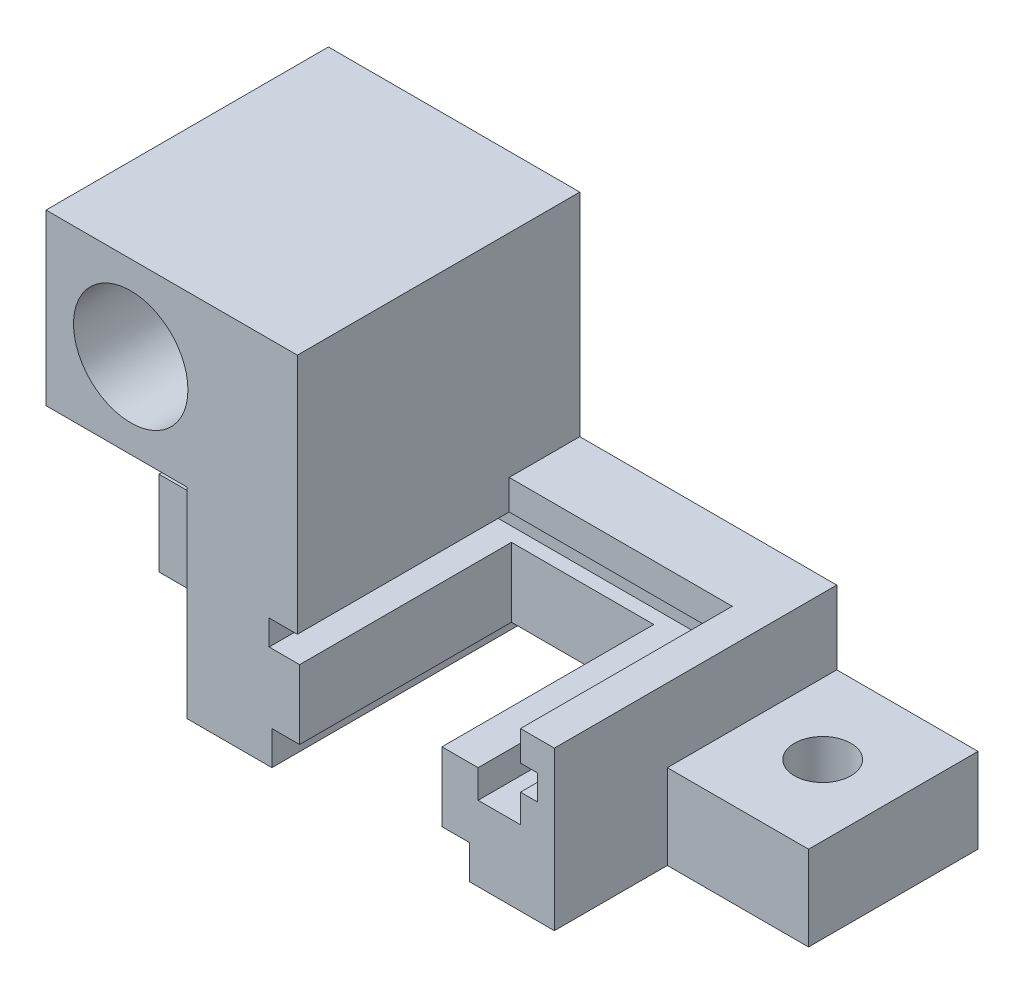
SolidWorks part; units mm, degrees
ref_plane "Front Plane" through (0, 0, 0) normal (0, 0, 1) x (1, 0, 0)
ref_plane "Top Plane" through (0, 0, 0) normal (0, 1, 0) x (1, 0, 0)
ref_plane "Right Plane" through (0, 0, 0) normal (1, 0, 0) x (0, 0, -1)
sketch "Sketch2" plane through (0, 0, 0) normal (0, 0, 1) x (1, 0, 0)
  line L0 (13, 0) -> (9.6353, 0) construction
  line L1 (-13, 5.6) -> (13, 5.6)
  line L2 (-13, 5.6) -> (-13, -5.6)
  line L3 (-13, -5.6) -> (13, -5.6)
  line L4 (13, 5.6) -> (13, -5.6)
  line L5 (0, -5.6) -> (0, -3.1467) construction
  dimension "D1" = 26
  dimension "D2" = 11.2
  dimension "D3" = 0
  dimension "D4" = 0
extrude "Boss-Extrude1" add sketch "Sketch2" along normal blind 20
sketch "Sketch6" plane through (0, 0, 20) normal (0, 0, 1) x (1, 0, 0)
  line L0 (-13, -5.6) -> (13, -5.6) construction
  line L1 (-7, -3.2) -> (7, -3.2)
  line L2 (-7, -3.2) -> (-7, -5.6)
  line L3 (-7, -5.6) -> (7, -5.6)
  line L4 (7, -3.2) -> (7, -5.6)
  line L5 (0, -5.6) -> (0, -4.6516) construction
  line L6 (0, -5.6) -> (0, -4.6516) construction
  dimension "D1" = 14
  dimension "D2" = 2.4
  dimension "D3" = 0
  dimension "D4" = 0
sketch "Sketch7" plane through (0, 0, 20) normal (0, 0, 1) x (1, 0, 0)
  line L0 (0, -3.2) -> (0, -2.2535) construction
  line L1 (-5.04, 1.7) -> (5.04, 1.7)
  line L2 (-5.04, 1.7) -> (-5.04, -3.2)
  line L3 (-5.04, -3.2) -> (5.04, -3.2)
  line L4 (5.04, 1.7) -> (5.04, -3.2)
  line L5 (-7, -3.2) -> (7, -3.2) construction
  dimension "D1" = 4.9
  dimension "D2" = 10.08
  dimension "D3" = 0
  dimension "D4" = 0
sketch "Sketch8" plane through (0, 0, 20) normal (0, 0, 1) x (1, 0, 0)
  line L0 (-5.04, 1.7) -> (5.04, 1.7) construction
  line L1 (-7.2, 3.48) -> (11.8, 3.48)
  line L2 (-7.2, 3.48) -> (-7.2, 1.7)
  line L3 (-7.2, 1.7) -> (11.8, 1.7)
  line L4 (11.8, 3.48) -> (11.8, 1.7)
  dimension "D1" = 19
  dimension "D2" = 1.78
  dimension "D3" = 7.2
  dimension "D4" = 0
sketch "Sketch9" plane through (0, 0, 20) normal (0, 0, 1) x (1, 0, 0)
  line L0 (-7.2, 3.48) -> (-7.2, 1.7) construction
  line L1 (-5.2, 5.6) -> (10.6, 5.6)
  line L2 (-5.2, 5.6) -> (-5.2, 3.48)
  line L3 (-5.2, 3.48) -> (10.6, 3.48)
  line L4 (10.6, 5.6) -> (10.6, 3.48)
  line L5 (11.8, 3.48) -> (11.8, 1.7) construction
  line L6 (-7.2, 3.48) -> (11.8, 3.48) construction
  line L7 (13, 5.6) -> (-13, 5.6) construction
  dimension "D1" = 2
  dimension "D2" = 1.2
  dimension "D3" = 0
  dimension "D4" = 0
sketch "Sketch10" plane through (0, 0, 20) normal (0, 0, 1) x (1, 0, 0)
  line L0 (11.8, 3.48) -> (11.8, 1.7) construction
  line L1 (7.6, 1.7) -> (10.6, 1.7)
  line L2 (7.6, 1.7) -> (7.6, -0.3)
  line L3 (7.6, -0.3) -> (10.6, -0.3)
  line L4 (10.6, 1.7) -> (10.6, -0.3)
  line L5 (-7.2, 1.7) -> (11.8, 1.7) construction
  dimension "D1" = 2
  dimension "D2" = 3
  dimension "D3" = 1.2
  dimension "D4" = 0
extrude "Cut-Extrude1" cut sketch "Sketch6" against normal blind 20
extrude "Cut-Extrude2" cut sketch "Sketch7" against normal blind 15
extrude "Cut-Extrude3" cut sketch "Sketch8" against normal blind 16
extrude "Cut-Extrude4" cut sketch "Sketch9" against normal blind 15
extrude "Cut-Extrude5" cut sketch "Sketch10" against normal blind 15
sketch "Sketch11" plane through (0, -5.6, 0) normal (0, -1, 0) x (1, 0, 0)
  line L0 (-13, 10) -> (-11.5021, 10) construction
  line L1 (-13, 20) -> (-13, 0) construction
  line L2 (-13, 0) -> (-7, 0) construction
  line L3 (-10, 0) -> (-10, 1.1276) construction
  line L4 (-11.55, 5) -> (-8.45, 5)
  arc A0 (-11.55, 5) -> (-8.45, 5) centre (-10, 5) cw
  dimension "D1" = 3.1
  dimension "D2" = 0
  dimension "D3" = 5
sketch "Sketch12" plane through (0, -5.6, 0) normal (0, -1, 0) x (1, 0, 0)
  line L0 (-11.5, 15) -> (-8.5, 15)
  line L1 (-10, 15) -> (-10, 15.7701) construction
  arc A0 (-11.5, 15) -> (-8.5, 15) centre (-10, 15) ccw
  dimension "D1" = 3
  dimension "D2" = 0
  dimension "D3" = 5
sketch "Sketch13" plane through (0, -5.6, 0) normal (0, -1, 0) x (1, 0, 0)
  line L0 (7, 0) -> (13, 0) construction
  line L1 (10, 0) -> (10, 1.2586) construction
  line L2 (13, 20) -> (13, 0) construction
  line L3 (13, 10) -> (11.9152, 10) construction
  line L4 (8.5, 5) -> (11.5, 5)
  line L5 (10, 5) -> (10, 6.238) construction
  arc A0 (8.5, 5) -> (11.5, 5) centre (10, 5) cw
  dimension "D1" = 3
  dimension "D2" = 1.5
  dimension "D3" = 5
sketch "Sketch14" plane through (0, -5.6, 0) normal (0, -1, 0) x (1, 0, 0)
  line L0 (8.45, 15) -> (11.55, 15)
  line L1 (13, 10) -> (11.9152, 10) construction
  line L2 (10, 15) -> (10, 16.0943) construction
  arc A0 (8.45, 15) -> (11.55, 15) centre (10, 15) ccw
  dimension "D1" = 3.1
  dimension "D2" = 5
  dimension "D3" = 0
revolve "Cut-Revolve3" cut sketch "Sketch11" angle 180 about L4
revolve "Revolve2" add sketch "Sketch12" angle 360 about L0
revolve "Cut-Revolve4" cut sketch "Sketch14" angle 360 about L0
revolve "Revolve3" add sketch "Sketch13" angle 360 about L4
sketch "Sketch15" plane through (-13, 0, 0) normal (-1, 0, 0) x (0, 0, 1)
  line L0 (0, 5.6) -> (0, -5.6) construction
  line L1 (12, 0.4) -> (0, 0.4)
  line L2 (12, 0.4) -> (12, -5.6)
  line L3 (12, -5.6) -> (0, -5.6)
  line L4 (0, 0.4) -> (0, -5.6)
  line L5 (20, -5.6) -> (0, -5.6) construction
  dimension "D1" = 0
  dimension "D2" = 0
  dimension "D3" = 6
  dimension "D4" = 12
extrude "Boss-Extrude2" add sketch "Sketch15" along normal blind 10
sketch "Sketch16" plane through (13, 0, 0) normal (1, 0, 0) x (0, 0, -1)
  line L0 (-20, -5.6) -> (0, -5.6) construction
  line L1 (-12, -5.6) -> (0, -5.6)
  line L2 (-12, -5.6) -> (-12, 0.4)
  line L3 (-12, 0.4) -> (0, 0.4)
  line L4 (0, -5.6) -> (0, 0.4)
  line L5 (0, -5.6) -> (0, 5.6) construction
  dimension "D1" = 0
  dimension "D2" = 0
  dimension "D3" = 6
  dimension "D4" = 12
extrude "Boss-Extrude3" add sketch "Sketch16" along normal blind 10
sketch "Sketch17" plane through (0, -5.6, 0) normal (0, -1, 0) x (1, 0, 0)
  line L0 (-23, 12) -> (-13, 12) construction
  line L1 (-18, 12) -> (-18, 10.8517) construction
  line L2 (-23, 0) -> (-23, 12) construction
  line L3 (-23, 6) -> (-21.8135, 6) construction
  circle A0 centre (-18, 6) radius 2
  dimension "D1" = 4
  dimension "D2" = 0
  dimension "D3" = 0
sketch "Sketch18" plane through (0, -5.6, 0) normal (0, -1, 0) x (1, 0, 0)
  line L0 (23, 12) -> (13, 12) construction
  line L1 (18, 12) -> (18, 10.2463) construction
  line L2 (23, 12) -> (23, 0) construction
  line L3 (23, 6) -> (21.7422, 6) construction
  circle A0 centre (18, 6) radius 2
  dimension "D1" = 4
  dimension "D2" = 0
  dimension "D3" = 0
extrude "Cut-Extrude6" cut sketch "Sketch17" against normal blind 12
extrude "Cut-Extrude7" cut sketch "Sketch18" against normal blind 12 contours A0
sketch "Sketch19" plane through (0, 5.6, 0) normal (0, 1, 0) x (1, 0, 0)
  line L1 (-5.2, -20) -> (-13, -20)
  line L2 (-5.2, -20) -> (-5.2, 0)
  line L3 (-5.2, 0) -> (-13, 0)
  line L4 (-13, -20) -> (-13, 0)
extrude "Boss-Extrude4" add sketch "Sketch19" along normal blind 15
sketch "Sketch20" plane through (-13, 0, 0) normal (-1, 0, 0) x (0, 0, 1)
  line L0 (0, 20.6) -> (20, 20.6) construction
  line L1 (20, 20.6) -> (0, 20.6)
  line L2 (20, 20.6) -> (20, 8.6)
  line L3 (20, 8.6) -> (0, 8.6)
  line L4 (0, 20.6) -> (0, 8.6)
  line L5 (0, 20.6) -> (0, 0.4) construction
  line L6 (20, 20.6) -> (20, -5.6) construction
  dimension "D1" = 12
  dimension "D2" = 0
  dimension "D3" = 0
  dimension "D4" = 0
extrude "Boss-Extrude5" add sketch "Sketch20" along normal blind 10
sketch "Sketch21" plane through (0, 0, 20) normal (0, 0, 1) x (1, 0, 0)
  line L0 (-23, 8.6) -> (-23, 20.6) construction
  line L1 (-23, 14.6) -> (-20.952, 14.6) construction
  circle A0 centre (-17, 14.6) radius 4.05
  point P8 (-14.6841, 9.3363)
  dimension "D1" = 8.1
  dimension "D2" = 0
  dimension "D3" = 6
extrude "Cut-Extrude8" cut sketch "Sketch21" against normal blind 18
sketch "Sketch22" plane through (-23, 0, 0) normal (-1, 0, 0) x (0, 0, 1)
  line L0 (0, 20.6) -> (0, 8.6) construction
  line L1 (0, 14.6) -> (1.4012, 14.6) construction
  circle A0 centre (11, 14.6) radius 1.5
  dimension "D1" = 3
  dimension "D2" = 0
  dimension "D3" = 11
extrude "Cut-Extrude9" cut sketch "Sketch22" against normal blind 5
